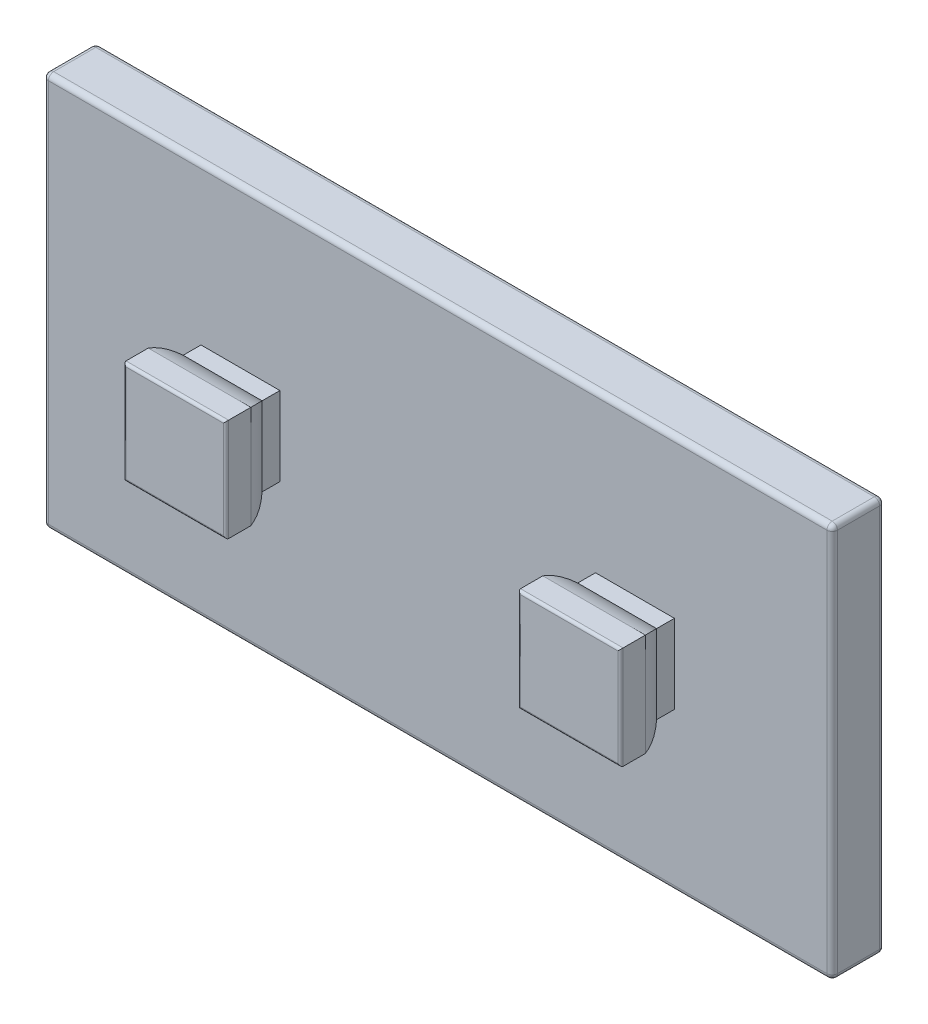
SolidWorks part; units mm, degrees
ref_plane "前视基准面" through (0, 0, 0) normal (0, 0, 1) x (1, 0, 0)
ref_plane "上视基准面" through (0, 0, 0) normal (0, 1, 0) x (1, 0, 0)
ref_plane "右视基准面" through (0, 0, 0) normal (1, 0, 0) x (0, 0, -1)
sketch "草图1" plane through (0, 0, 0) normal (0, 0, 1) x (1, 0, 0)
  line L1 (-7.5, -7.5) -> (22.5, -7.5)
  line L2 (-7.5, -7.5) -> (-7.5, 7.5)
  line L3 (-7.5, 7.5) -> (22.5, 7.5)
  line L4 (22.5, -7.5) -> (22.5, 7.5)
extrude "凸台-拉伸1" add sketch "草图1" against normal blind 2
sketch "草图2" plane through (0, 0, 0) normal (0, 0, 1) x (1, 0, 0)
  line L1 (-1.5, -1.5) -> (1.5, -1.5)
  line L2 (-1.5, -1.5) -> (-1.5, 1.5)
  line L3 (-1.5, 1.5) -> (1.5, 1.5)
  line L4 (1.5, -1.5) -> (1.5, 1.5)
extrude "凸台-拉伸2" add sketch "草图2" along normal blind 1
sketch "草图3" plane through (0, 0, 0) normal (0, 1, 0) x (1, 0, 0)
  line L0 (-1.95, -2.5) -> (1.95, -2.5)
  line L1 (-1.95, -2.5) -> (-1.95, -1.5556)
  line L2 (-1.5, -1) -> (-1.5, 0) construction
  line L3 (-1.5, -0.6771) -> (1.5, -0.6771)
  line L4 (1.95, -2.5) -> (1.95, -1.5556)
  arc A0 (1.95, -1.5556) -> (1.5, -0.6771) centre (0, -2) ccw
  arc A1 (-1.5, -0.6771) -> (-1.95, -1.5556) centre (0, -2) ccw
extrude "凸台-拉伸3" add sketch "草图3" along normal blind 2 and the other way blind 2
sketch "草图4" plane through (0, 0, 0) normal (1, 0, 0) x (0, 0, -1)
  line L0 (-2.5, 1.95) -> (-1.5556, 1.95)
  line L1 (-2.5, 1.95) -> (-2.5, 2)
  line L2 (-2.5, -2) -> (-2.5, 2) construction
  line L3 (-2.5, 2) -> (-0.6771, 2)
  line L4 (-0.6771, 2) -> (-0.6771, 1.5)
  line L5 (-2.5, -2) -> (-0.6771, -2)
  line L6 (-0.6771, -2) -> (-0.6771, -1.5)
  line L7 (-2.5, -1.95) -> (-1.5556, -1.95)
  line L8 (-2.5, -1.95) -> (-2.5, -2)
  arc A0 (-0.6771, 1.5) -> (-1.5556, 1.95) centre (-2, 0) ccw
  arc A2 (-1.5556, -1.95) -> (-0.6771, -1.5) centre (-2, 0) ccw
extrude "切除-拉伸1" cut sketch "草图4" against normal up to next and the other way up to next
fillet "圆角1" radius 0.1 4 edges at (0, -1.95, 2.5) (-1.95, 0, 2.5) (0, 1.95, 2.5) (1.95, 0, 2.5)
ref_plane "基准面1" through (7.5, 0, 0) normal (1, 0, 0) x (0, 0, -1)
mirror "镜向1" about plane through (7.5, 0, 0) normal (1, 0, 0) of "凸台-拉伸3", "凸台-拉伸2", "切除-拉伸1", "圆角1"
fillet "圆角3" radius 0.2 12 edges at (7.5, -7.5, -2) (7.5, -7.5, 0) (-7.5, -7.5, -1) (-7.5, 0, -2) (-7.5, 0, 0) (22.5, 0, -2) (22.5, -7.5, -1) (22.5, 0, 0) (-7.5, 7.5, -1) (7.5, 7.5, -2) (22.5, 7.5, -1) (7.5, 7.5, 0)
